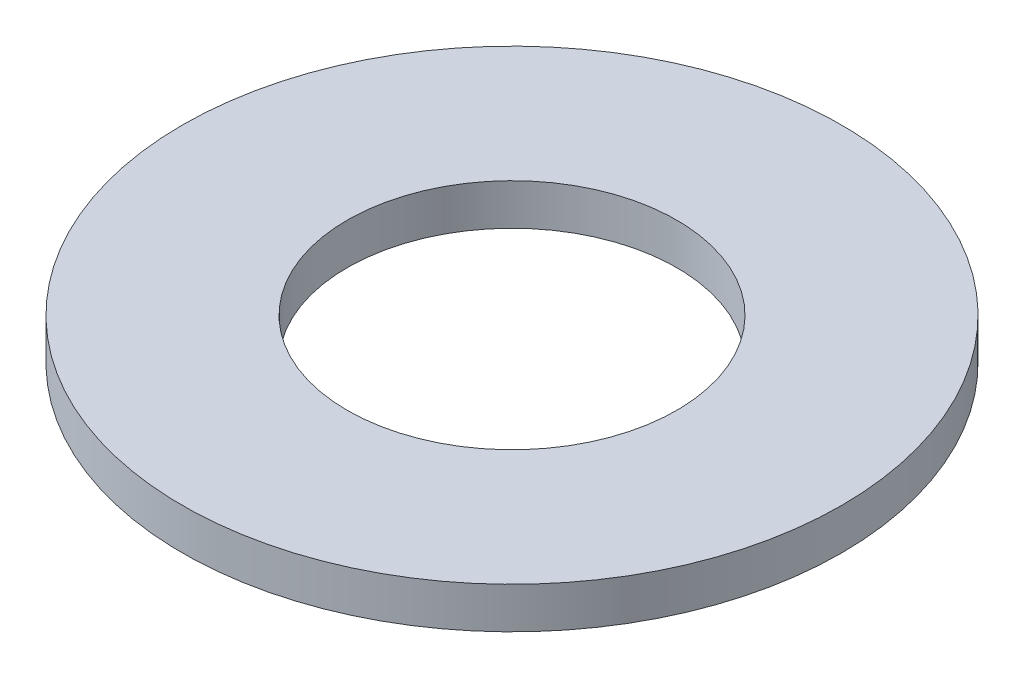
SolidWorks part; units mm, degrees
ref_plane "Front Plane" through (0, 0, 0) normal (0, 0, 1) x (1, 0, 0)
ref_plane "Top Plane" through (0, 0, 0) normal (0, 1, 0) x (1, 0, 0)
ref_plane "Right Plane" through (0, 0, 0) normal (1, 0, 0) x (0, 0, -1)
sketch "Sketch1" plane through (0, 0, 0) normal (0, 1, 0) x (1, 0, 0)
  circle A0 centre (0, 0) radius 8
  dimension "D1" = 16
extrude "Extrude-Thin1" add sketch "Sketch1" along normal blind 2 thin
